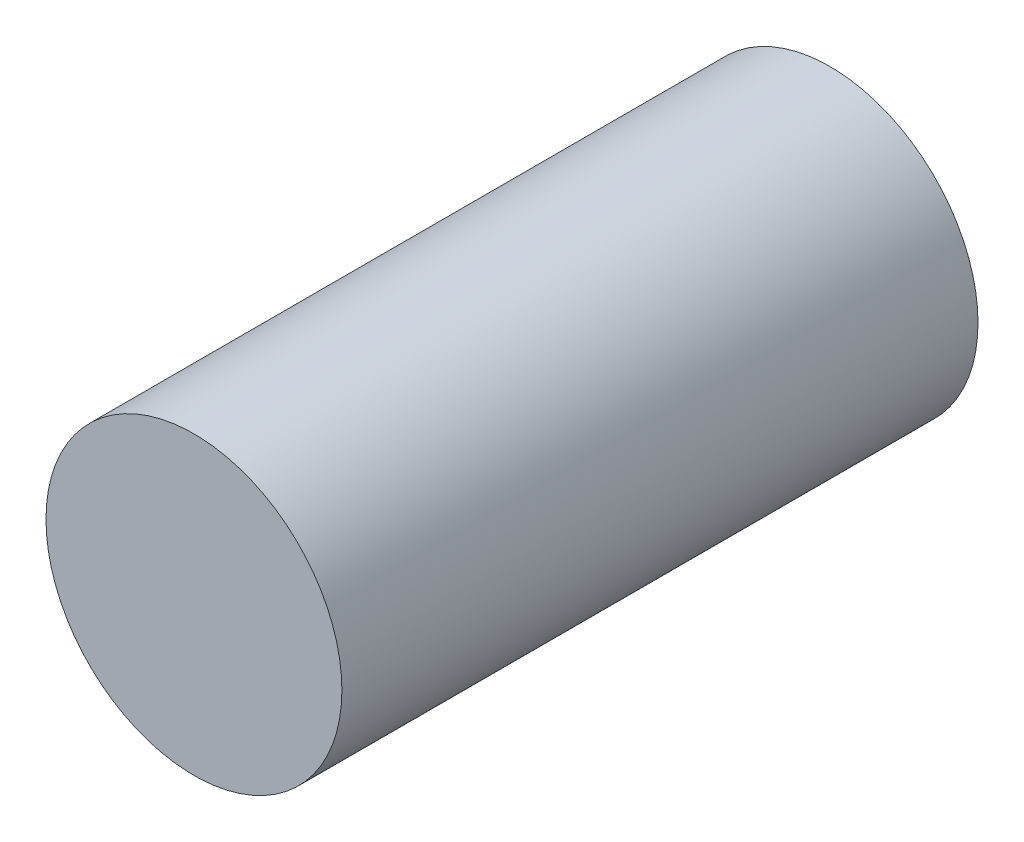
SolidWorks part; units mm, degrees
material "Alloy Steel"
ref_plane "Front Plane" through (0, 0, 0) normal (0, 0, 1) x (1, 0, 0)
ref_plane "Top Plane" through (0, 0, 0) normal (0, 1, 0) x (1, 0, 0)
ref_plane "Right Plane" through (0, 0, 0) normal (1, 0, 0) x (0, 0, -1)
sketch "Sketch1" plane through (0, 0, 0) normal (0, 0, 1) x (1, 0, 0)
  circle A0 centre (0, 0) radius 6.35
  dimension "D1" = 12.7
extrude "Boss-Extrude1" add sketch "Sketch1" along normal blind 27.3
